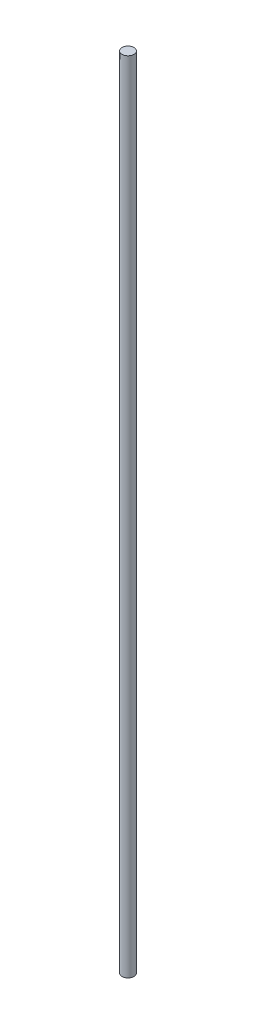
SolidWorks part; units mm, degrees
material "Thornel Mat VMA"
ref_plane "Front Plane" through (0, 0, 0) normal (0, 0, 1) x (1, 0, 0)
ref_plane "Top Plane" through (0, 0, 0) normal (0, 1, 0) x (1, 0, 0)
ref_plane "Right Plane" through (0, 0, 0) normal (1, 0, 0) x (0, 0, -1)
sketch "Sketch1" plane through (0, 0, 0) normal (0, 1, 0) x (1, 0, 0)
  circle A0 centre (0, 0) radius 1.5
  dimension "D1" = 3
extrude "Boss-Extrude1" add sketch "Sketch1" along normal mid plane 200
